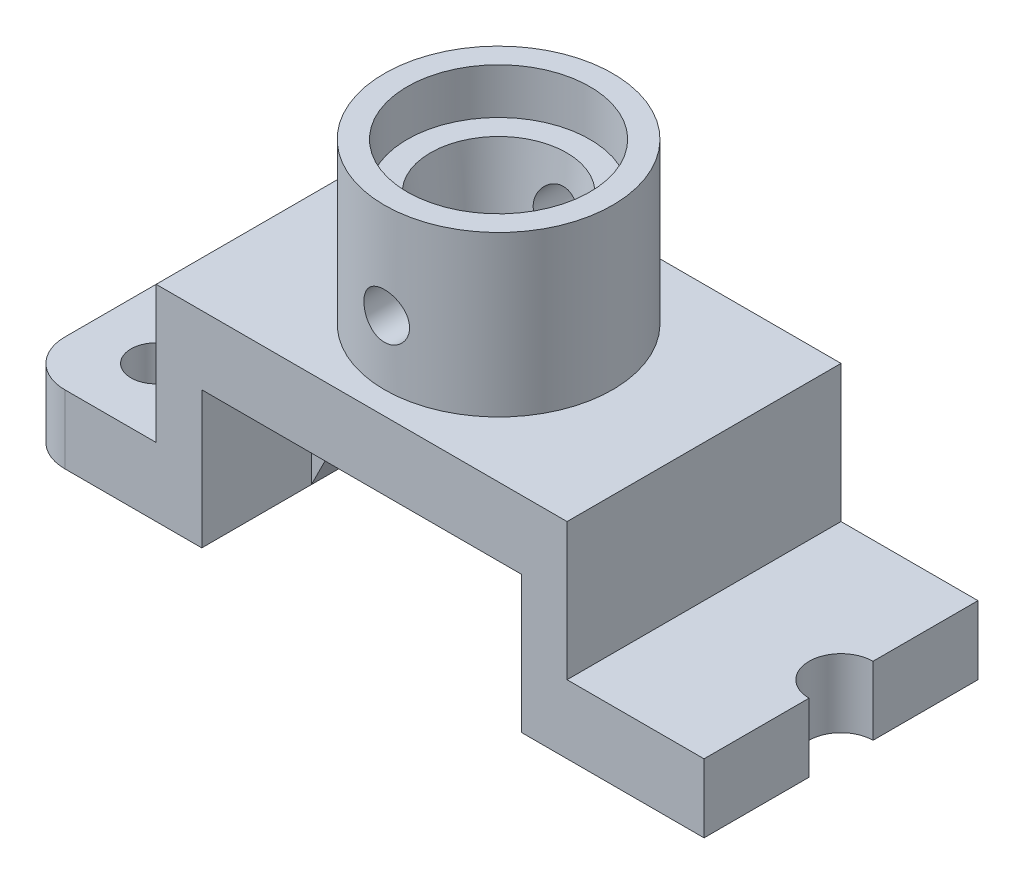
SolidWorks part; units mm, degrees
ref_plane "Front Plane" through (0, 0, 0) normal (0, 0, 1) x (1, 0, 0)
ref_plane "Top Plane" through (0, 0, 0) normal (0, 1, 0) x (1, 0, 0)
ref_plane "Right Plane" through (0, 0, 0) normal (1, 0, 0) x (0, 0, -1)
sketch "Sketch1" plane through (0, 0, 0) normal (0, 0, 1) x (1, 0, 0)
  line L0 (-75, 0) -> (-35, 0)
  line L1 (-35, 0) -> (-35, 30)
  line L2 (-35, 30) -> (35, 30)
  line L3 (35, 30) -> (35, 0)
  line L4 (35, 0) -> (75, 0)
  line L5 (75, 0) -> (75, 15)
  line L6 (75, 15) -> (45, 15)
  line L7 (45, 15) -> (45, 45)
  line L8 (45, 45) -> (-45, 45)
  line L9 (-45, 45) -> (-45, 15)
  line L10 (-45, 15) -> (-75, 15)
  line L11 (-75, 15) -> (-75, 0)
  line L12 (-35, 0) -> (-20, 30)
  line L13 (20, 30) -> (35, 0)
  line L14 (-20, 30) -> (-35, 30)
  line L15 (-35, 0) -> (-20, 30)
  point P16 (0, 30)
  dimension "D1" = 70
  dimension "D2" = 40
  dimension "D3" = 45
  dimension "D4" = 15
  dimension "D5" = 90
  dimension "D6" = 15
  dimension "D7" = 15
  dimension "D8" = 15
extrude "Boss-Extrude1" add sketch "Sketch1" along normal mid plane 60 contours L10 L11 L0 L1 L2 L3 L4 L5 L6 L7 L8 L9
sketch "Sketch2" plane through (0, 0, 0) normal (0, 0, 1) x (1, 0, 0)
  line L0 (20, 30) -> (35, 0) construction
  line L1 (-35, 0) -> (-20, 30) construction
  line L2 (35, 30) -> (35, 0) construction
  line L3 (-35, 0) -> (-35, 30) construction
  line L4 (-35, 30) -> (35, 30) construction
  line L5 (20, 30) -> (35, 0)
  line L6 (-35, 0) -> (-20, 30)
  line L7 (35, 30) -> (35, 0)
  line L8 (-35, 0) -> (-35, 30)
  line L9 (-35, 30) -> (-20, 30)
  line L10 (20, 30) -> (35, 30)
extrude "Boss-Extrude2" add sketch "Sketch2" along normal mid plane 12
sketch "Sketch3" plane through (0, 15, 0) normal (0, 1, 0) x (1, 0, 0)
  line L0 (-45, -30) -> (-75, -30) construction
  line L1 (-45, 30) -> (-75, 30) construction
  circle A0 centre (-60, 15) radius 5.51
  circle A1 centre (-60, -15) radius 5.51
  dimension "D2" = 15
  dimension "D1" = 30
  dimension "D3" = 15
  dimension "D4" = 15
extrude "Cut-Extrude1" cut sketch "Sketch3" against normal through all
fillet "Fillet1" radius 10 2 edges at (-75, 7.5, -30) (-75, 7.5, 30)
sketch "Sketch4" plane through (0, 15, 0) normal (0, 1, 0) x (1, 0, 0)
  circle A0 centre (75, 0) radius 7
  dimension "D1" = 14
  dimension "D2" = 30
extrude "Cut-Extrude2" cut sketch "Sketch4" against normal blind 42
sketch "Sketch5" plane through (0, 45, 0) normal (0, 1, 0) x (1, 0, 0)
  line L0 (-45, 0) -> (45, 0) construction
  circle A0 centre (0, 0) radius 25
  dimension "D1" = 50
extrude "Boss-Extrude3" add sketch "Sketch5" along normal blind 35
sketch "Sketch6" plane through (0, 80, 0) normal (0, 1, 0) x (1, 0, 0)
  circle A0 centre (0, 0) radius 20
  dimension "D1" = 40
extrude "Cut-Extrude3" cut sketch "Sketch6" against normal blind 10
sketch "Sketch7" plane through (0, 70, 0) normal (0, 1, 0) x (1, 0, 0)
  circle A0 centre (0, 0) radius 15
  dimension "D1" = 30
sketch "Sketch8" plane through (0, 30, 0) normal (0, -1, 0) x (1, 0, 0)
  line L0 (-35, 0) -> (35, 0) construction
  circle A0 centre (0, 0) radius 10
  dimension "D1" = 20
extrude "Cut-Extrude4" cut sketch "Sketch8" against normal up to next (40 mm away) draft 7 draft outward yes
sketch "Sketch9" plane through (0, 0, 0) normal (0, 0, 1) x (1, 0, 0)
  line L0 (25, 80) -> (-25, 80) construction
  circle A0 centre (0, 59) radius 5
  dimension "D1" = 10
  dimension "D2" = 21
extrude "Cut-Extrude5" cut sketch "Sketch9" against normal through all both and the other way through all
